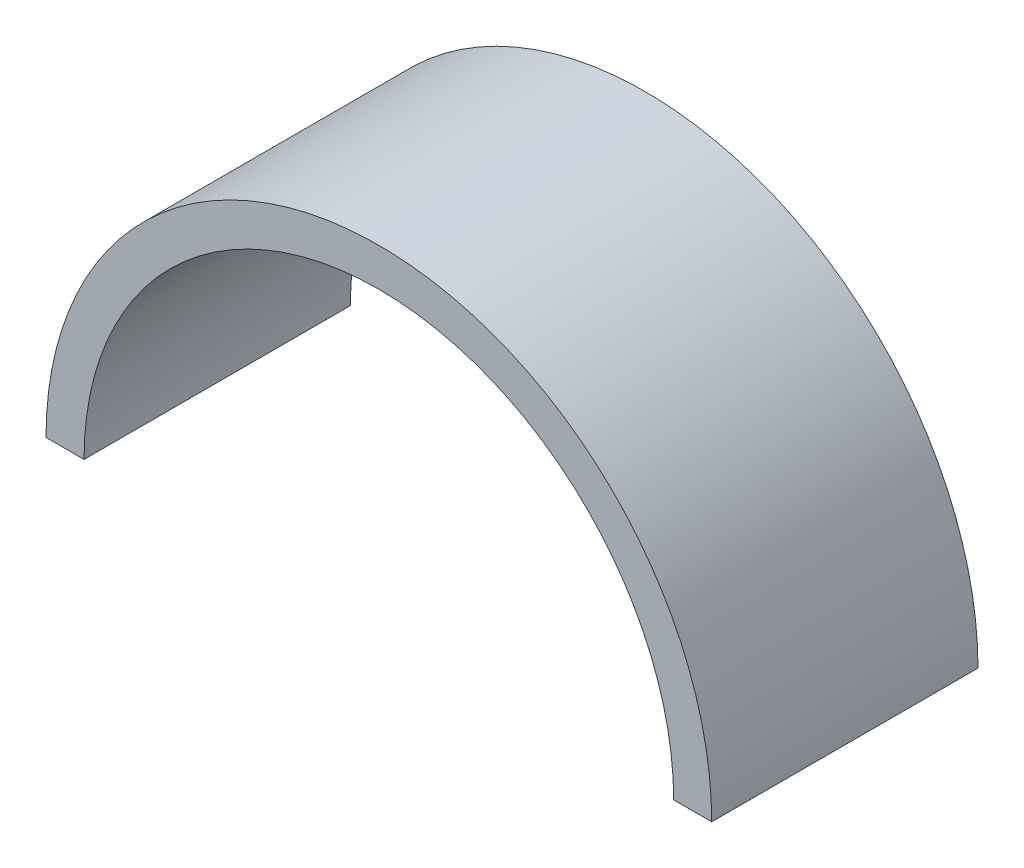
SolidWorks part; units mm, degrees
ref_plane "Alzado" through (0, 0, 0) normal (0, 0, 1) x (1, 0, 0)
ref_plane "Planta" through (0, 0, 0) normal (0, 1, 0) x (1, 0, 0)
ref_plane "Vista lateral" through (0, 0, 0) normal (1, 0, 0) x (0, 0, -1)
sketch "Croquis1" plane through (0, 0, 0) normal (0, 0, 1) x (1, 0, 0)
  line L0 (-17.5, 0) -> (-15.5, 0)
  line L1 (15.5, 0) -> (17.5, 0)
  arc A0 (15.5, 0) -> (-15.5, 0) centre (0, 0) ccw
  arc A1 (17.5, 0) -> (-17.5, 0) centre (0, 0) ccw
  circle A2 centre (0, 0) radius 17.5 construction
  circle A3 centre (0, 0) radius 15.5 construction
  dimension "D1" = 31
  dimension "D2" = 2
extrude "Saliente-Extruir1" add sketch "Croquis1" along normal blind 14
